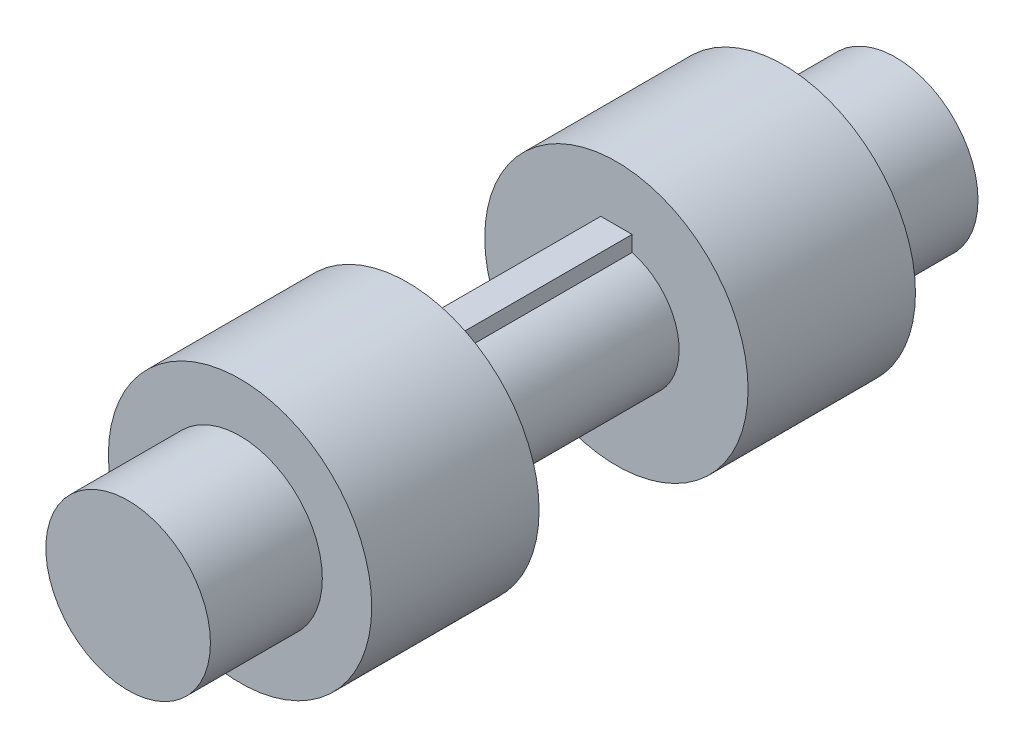
SolidWorks part; units mm, degrees
ref_plane "Front Plane" through (0, 0, 0) normal (0, 0, 1) x (1, 0, 0)
ref_plane "Top Plane" through (0, 0, 0) normal (0, 1, 0) x (1, 0, 0)
ref_plane "Right Plane" through (0, 0, 0) normal (1, 0, 0) x (0, 0, -1)
sketch "Sketch1" plane through (0, 0, 0) normal (0, 0, 1) x (1, 0, 0)
  circle A0 centre (0, 0) radius 12.5
  dimension "D1" = 25
extrude "Boss-Extrude1" add sketch "Sketch1" against normal blind 17
sketch "Sketch2" plane through (0, 0, 0) normal (0, 0, 1) x (1, 0, 0)
  circle A0 centre (0, 0) radius 20
  dimension "D1" = 40
extrude "Boss-Extrude2" add sketch "Sketch2" along normal blind 25.425
sketch "Sketch3" plane through (0, 0, 25.425) normal (0, 0, 1) x (1, 0, 0)
  circle A0 centre (0, 0) radius 9.525
  dimension "D1" = 19.05
extrude "Boss-Extrude3" add sketch "Sketch3" along normal blind 31.75
sketch "Sketch9" plane through (0, 0, 57.175) normal (0, 0, 1) x (1, 0, 0)
  line L0 (0, 0) -> (0, 16.0652) construction
  line L2 (2.3812, 11.6038) -> (-2.3813, 11.6038)
  line L3 (2.3812, 11.6038) -> (2.3812, 9.2225)
  line L4 (2.3812, 9.2225) -> (-2.3813, 9.2225)
  line L5 (-2.3813, 11.6038) -> (-2.3813, 9.2225)
  line L6 (2.3812, 11.6038) -> (-2.3813, 9.2225) construction
  line L7 (2.3812, 9.2225) -> (-2.3813, 11.6038) construction
  circle A0 centre (0, 0) radius 9.525 construction
  point P3 (0, 10.4132)
  dimension "D1" = 4.7625
  dimension "D2" = 2.3813
extrude "Boss-Extrude6" add sketch "Sketch9" against normal up to surface (31.75 mm away) up to face at (9.525, 0, 25.425)
sketch "Sketch4" plane through (0, 0, 57.175) normal (0, 0, 1) x (1, 0, 0)
  circle A0 centre (0, 0) radius 20
  dimension "D1" = 40
extrude "Boss-Extrude4" add sketch "Sketch4" along normal blind 25.425
sketch "Sketch5" plane through (0, 0, 82.6) normal (0, 0, 1) x (1, 0, 0)
  circle A0 centre (0, 0) radius 12.5
  dimension "D1" = 25
extrude "Boss-Extrude5" add sketch "Sketch5" along normal blind 17 contours A0
